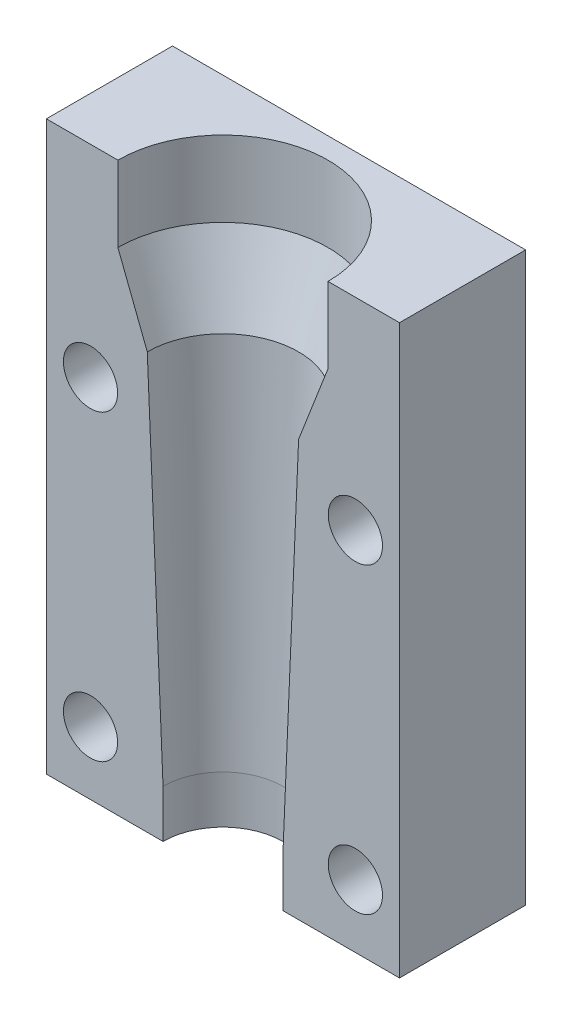
SolidWorks part; units mm, degrees
ref_plane "Front Plane" through (0, 0, 0) normal (0, 0, 1) x (1, 0, 0)
ref_plane "Top Plane" through (0, 0, 0) normal (0, 1, 0) x (1, 0, 0)
ref_plane "Right Plane" through (0, 0, 0) normal (1, 0, 0) x (0, 0, -1)
sketch "Sketch4" plane through (0, 0, 0) normal (0, 0, 1) x (1, 0, 0)
  line L1 (-14, 22.5) -> (14, 22.5)
  line L2 (-14, 22.5) -> (-14, -22.5)
  line L3 (-14, -22.5) -> (14, -22.5)
  line L4 (14, 22.5) -> (14, -22.5)
  line L5 (-14, 22.5) -> (14, -22.5) construction
  line L6 (-14, -22.5) -> (14, 22.5) construction
  point P0 (0, 0)
  dimension "D1" = 28
  dimension "D2" = 45
extrude "Boss-Extrude2" add sketch "Sketch4" along normal blind 10
sketch "Sketch5" plane through (0, 0, 10) normal (0, 0, 1) x (1, 0, 0)
  line L0 (0, 0) -> (0, 24.6891) construction
  line L1 (14, 22.5) -> (-14, 22.5) construction
  line L2 (-14, -22.5) -> (14, -22.5) construction
  line L3 (0, 22.5) -> (8.33, 22.5)
  line L4 (8.33, 22.5) -> (8.33, 16.5)
  line L5 (8.33, 16.5) -> (6, 10.5)
  line L6 (6, 10.5) -> (4.75, -18.71)
  line L7 (4.75, -18.71) -> (4.75, -22.5)
  line L8 (4.75, -22.5) -> (0, -22.5)
  line L10 (0, 22.5) -> (0, -22.5)
  dimension "D1" = 6
  dimension "D2" = 6
  dimension "D3" = 41.21
  dimension "D4" = 16.66
  dimension "D5" = 12
  dimension "D6" = 9.5
revolve "Cut-Revolve1" cut sketch "Sketch5" angle 360 about L0
sketch "Sketch6" plane through (0, 0, 10) normal (0, 0, 1) x (1, 0, 0)
  line L0 (-10.5, 22.5) -> (-10.5, -22.5) construction
  line L1 (-8.33, 22.5) -> (-14, 22.5) construction
  line L2 (-14, -22.5) -> (-4.75, -22.5) construction
  line L3 (10.5, 22.5) -> (10.5, -22.5) construction
  line L4 (14, 22.5) -> (8.33, 22.5) construction
  line L5 (4.75, -22.5) -> (14, -22.5) construction
  line L6 (-14, 22.5) -> (-14, -22.5) construction
  line L7 (0, 0) -> (0, 27.9587) construction
  circle A0 centre (-10.5, 6.5) radius 2.15
  circle A1 centre (-10.5, -17.5) radius 2.15
  circle A2 centre (10.5, 6.5) radius 2.15
  circle A3 centre (10.5, -17.5) radius 2.15
  dimension "D1" = 4.3
  dimension "D2" = 5
  dimension "D3" = 16
  dimension "D4" = 3.5
extrude "Cut-Extrude1" cut sketch "Sketch6" against normal blind 6
sketch "Sketch7" plane through (0, 0, 0) normal (0, 0, -1) x (-1, 0, 0)
  line L0 (0, 22.5) -> (0, -22.5) construction
  line L1 (-14, 22.5) -> (14, 22.5) construction
  line L2 (14, -22.5) -> (-14, -22.5) construction
  line L3 (-10, 12.5) -> (10, 12.5) construction
  circle A0 centre (-10, 12.5) radius 2.75
  circle A1 centre (10, 12.5) radius 2.75
  point P9 (0, 12.5)
  point P12 (8.03, 12.9438)
  dimension "D1" = 5.5
  dimension "D2" = 20
  dimension "D3" = 10
extrude "Cut-Extrude2" cut sketch "Sketch7" against normal blind 6
